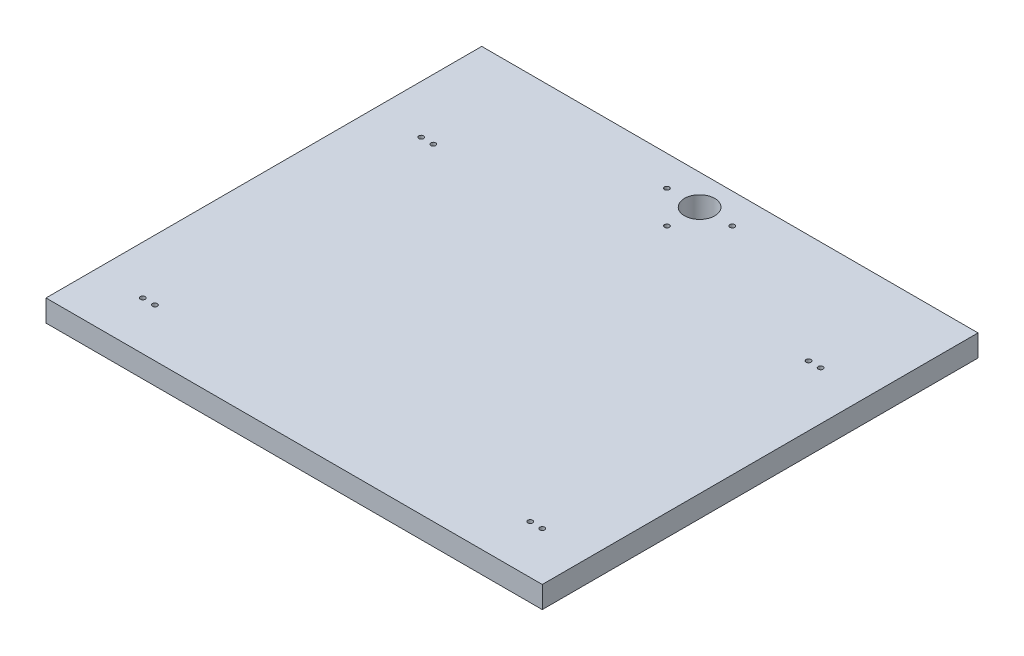
SolidWorks part; units mm, degrees
material "Beech"
ref_plane "Front Plane" through (0, 0, 0) normal (0, 0, 1) x (1, 0, 0)
ref_plane "Top Plane" through (0, 0, 0) normal (0, 1, 0) x (1, 0, 0)
ref_plane "Right Plane" through (0, 0, 0) normal (1, 0, 0) x (0, 0, -1)
sketch "Sketch1" plane through (0, 0, 0) normal (0, 1, 0) x (1, 0, 0)
  line L1 (0, 0) -> (410, 0)
  line L2 (0, 0) -> (0, 360)
  line L3 (0, 360) -> (410, 360)
  line L4 (410, 0) -> (410, 360)
  dimension "D1" = 360
  dimension "D2" = 410
extrude "Boss-Extrude1" add sketch "Sketch1" along normal blind 18
sketch "Sketch2" plane through (0, 18, 0) normal (0, 1, 0) x (1, 0, 0)
  line L0 (0, 360) -> (0, 0) construction
  line L3 (410, 360) -> (0, 360) construction
  circle A0 centre (205, 335) radius 12.5
  dimension "D1" = 25
  dimension "D2" = 205
  dimension "D3" = 25
extrude "Camera Stand to Base (Profile)" cut sketch "Sketch2" against normal through all
sketch "Sketch3" plane through (0, 18, 0) normal (0, 1, 0) x (1, 0, 0)
  line L0 (0, 0) -> (410, 0) construction
  line L2 (0, 360) -> (0, 0) construction
  line L3 (410, 0) -> (410, 360) construction
  circle A0 centre (40, 40) radius 2
  circle A1 centre (50, 40) radius 2
  circle A2 centre (360, 40) radius 2
  circle A3 centre (370, 40) radius 2
  circle A4 centre (370, 270) radius 2
  circle A5 centre (360, 270) radius 2
  circle A6 centre (40, 270) radius 2
  circle A7 centre (50, 270) radius 2
  point P0 (40, 40)
  point P1 (50, 40)
  point P2 (360, 40)
  point P3 (370, 40)
  point P4 (40, 270)
  point P5 (50, 270)
  point P6 (360, 270)
  point P7 (370, 270)
  point P8 (-131.1028, 259.9763)
  dimension "D7" = 4
  dimension "D1" = 10
  dimension "D2" = 10
  dimension "D3" = 40
  dimension "D4" = 230
  dimension "D5" = 40
  dimension "D6" = 40
extrude "Cut-Extrude2" cut sketch "Sketch3" against normal through all
sketch "Sketch5" plane through (0, 0, 0) normal (0, -1, 0) x (-1, 0, 0)
  point P0 (-205, 335)
sketch "Sketch6" plane through (0, 0, 0) normal (0, -1, 0) x (1, 0, 0)
  line L5 (410, -360) -> (0, -360) construction
  circle A0 centre (205, -308) radius 2
  circle A1 centre (178, -335) radius 2
  circle A2 centre (232, -335) radius 2
  circle A3 centre (205, -335) radius 12.5 construction
  dimension "D3" = 4
  dimension "D1" = 25
  dimension "D2" = 52
  dimension "D4" = 27
  dimension "D5" = 54
extrude "Camera Stand to Base (Screw)" cut sketch "Sketch6" against normal through all
sketch "Sketch7" plane through (0, 0, 0) normal (0, -1, 0) x (1, 0, 0)
  circle A0 centre (40, -40) radius 4
  circle A1 centre (50, -40) radius 4
  circle A2 centre (360, -40) radius 4
  circle A3 centre (370, -40) radius 4
  circle A4 centre (370, -270) radius 4
  circle A5 centre (360, -270) radius 4
  circle A6 centre (50, -270) radius 4
  circle A7 centre (40, -270) radius 4
  circle A8 centre (178, -335) radius 4
  circle A9 centre (205, -308) radius 4
  circle A10 centre (232, -335) radius 4
  dimension "D1" = 8
extrude "Cut-Extrude3" cut sketch "Sketch7" against normal blind 8
